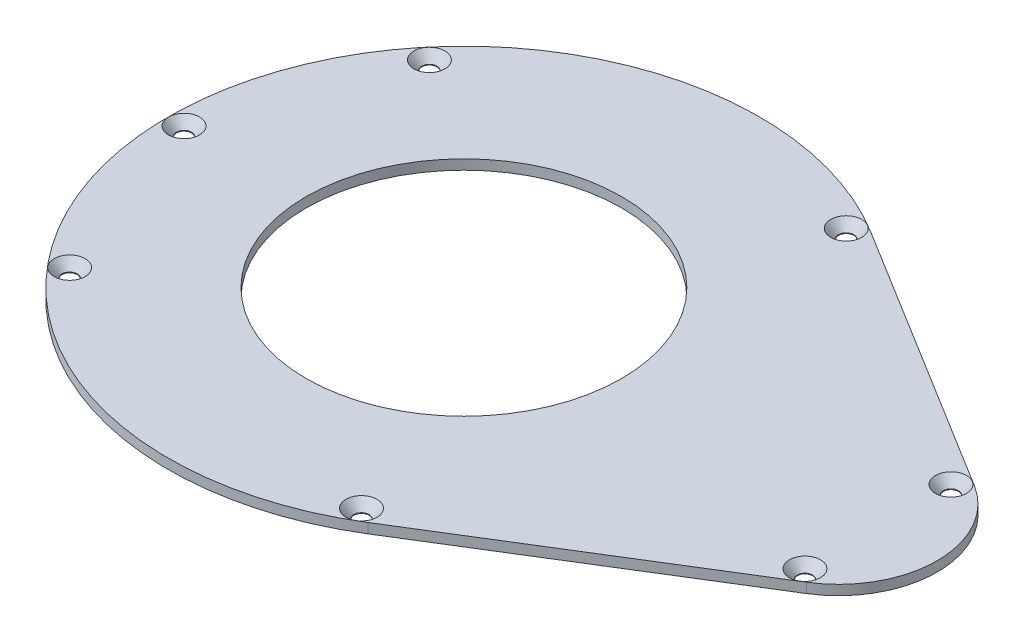
SolidWorks part; units mm, degrees
material "6061-T6 (SS)"
ref_plane "Front Plane" through (0, 0, 0) normal (0, 0, 1) x (1, 0, 0)
ref_plane "Top Plane" through (0, 0, 0) normal (0, 1, 0) x (1, 0, 0)
ref_plane "Right Plane" through (0, 0, 0) normal (1, 0, 0) x (0, 0, -1)
sketch "Sketch1" plane through (0, 0, 0) normal (0, 1, 0) x (1, 0, 0)
  circle A0 centre (0, 0) radius 47.625
  dimension "D1" = 95.25
extrude "Boss-Extrude1" add sketch "Sketch1" along normal blind 24.13
sketch "Sketch2" plane through (0, 0, 0) normal (0, -1, 0) x (1, 0, 0)
  circle A0 centre (0, 0) radius 46.0375
  circle A1 centre (0, 0) radius 47.625 construction
  dimension "D1" = 1.5875
extrude "Cut-Extrude1" cut sketch "Sketch2" against normal offset from surface (20.955 mm away) 3.175 up to face at (0, 24.13, 47.625)
sketch "Sketch3" plane through (0, 20.955, 0) normal (0, -1, 0) x (1, 0, 0)
  circle A0 centre (0, 0) radius 30.48
  dimension "D1" = 60.96
extrude "Cut-Extrude2" cut sketch "Sketch3" against normal through all
sketch "Sketch4" plane through (0, 24.13, 0) normal (0, 1, 0) x (1, 0, 0)
  line L0 (25.0479, 40.5061) -> (68.7175, 13.502)
  line L1 (25.0479, -40.5061) -> (68.7175, -13.502)
  arc A0 (68.7175, -13.502) -> (68.7175, 13.502) centre (60.3682, 0) ccw
  circle A1 centre (0, 0) radius 47.625 construction
  arc A2 (25.0479, -40.5061) -> (25.0479, 40.5061) centre (0, 0) ccw
  dimension "D2" = 31.75
  dimension "D1" = 60.3682
extrude "Boss-Extrude2" add sketch "Sketch4" against normal up to surface (24.13 mm away) up to face at (0, 0, -46.0375)
sketch "Sketch5" plane through (0, 0, 0) normal (0, -1, 0) x (1, 0, 0)
  line L4 (24.2129, -39.1559) -> (67.8825, -12.1518)
  line L5 (67.8825, 12.1518) -> (24.2129, 39.1559)
  line L6 (24.2129, -39.1559) -> (67.8825, -12.1518)
  line L7 (67.8825, 12.1518) -> (24.2129, 39.1559)
  circle A1 centre (0, 0) radius 46.0375 construction
  arc A2 (67.8825, -12.1518) -> (67.8825, 12.1518) centre (60.3682, 0) ccw
  arc A3 (67.8825, -12.1518) -> (67.8825, 12.1518) centre (60.3682, 0) ccw
  arc A4 (24.2129, -39.1559) -> (24.2129, 39.1559) centre (0, 0) ccw
  dimension "D1" = 1.5875
extrude "Cut-Extrude3" cut sketch "Sketch5" against normal up to surface (20.955 mm away) up to face at (0, 20.955, -30.48)
sketch "Sketch6" plane through (0, 20.955, 0) normal (0, -1, 0) x (1, 0, 0)
  line L0 (67.8825, 12.1518) -> (24.2129, 39.1559) construction
  line L1 (24.2129, -39.1559) -> (67.8825, -12.1518) construction
  line L2 (53.1536, 21.2598) -> (46.0477, 25.6539)
  line L3 (46.0477, -25.6539) -> (53.1536, -21.2598)
  line L4 (68.7175, 13.502) -> (25.0479, 40.5061) construction
  line L5 (25.0479, -40.5061) -> (68.7175, -13.502) construction
  line L6 (68.7175, 13.502) -> (46.8827, 27.0041)
  line L7 (46.8827, -27.0041) -> (68.7175, -13.502)
  line L8 (46.0477, 25.6539) -> (46.8827, 27.0041)
  line L9 (46.8827, -27.0041) -> (46.0477, -25.6539)
  arc A0 (53.332, 10.5727) -> (53.332, -10.5727) centre (60.3682, 0) ccw
  arc A2 (68.7175, -13.502) -> (68.7175, 13.502) centre (60.3682, 0) ccw construction
  arc A3 (68.7175, -13.502) -> (68.7175, 13.502) centre (60.3682, 0) ccw
  arc A4 (53.1536, -21.2598) -> (53.332, -10.5727) centre (49.8138, -15.859) ccw
  arc A5 (53.1536, 21.2598) -> (53.332, 10.5727) centre (49.8138, 15.859) cw
  dimension "D1" = 6.35
  dimension "D2" = 12.7
extrude "Boss-Extrude3" add sketch "Sketch6" along normal blind 3.81
sketch "Sketch7" plane through (0, 24.13, 0) normal (0, 1, 0) x (1, 0, 0)
  circle A0 centre (60.3682, 0) radius 11.176
  dimension "D1" = 22.352
extrude "Cut-Extrude4" cut sketch "Sketch7" against normal blind 3.81
chamfer "Chamfer1" distance 0.762 angle 45 1 edges at (60.3682, 24.13, 11.176)
sketch "Sketch8" plane through (0, 20.32, 0) normal (0, 1, 0) x (1, 0, 0)
  circle A0 centre (60.3682, 0) radius 5.08
  dimension "D1" = 10.16
extrude "Cut-Extrude5" cut sketch "Sketch8" against normal through all
hole_wizard "CSK for M2.5 Flat Head Machine Screw1" positions "Sketch10" profile "Sketch9" countersink size "M2.5" standard "Ansi Metric" end condition through all
sketch "Sketch10" plane through (0, 17.145, 0) normal (0, -1, 0) x (1, 0, 0)
  line L0 (60.3682, 0) -> (76.2432, 0) construction
  arc A0 (68.7175, -13.502) -> (68.7175, 13.502) centre (60.3682, 0) ccw construction
  point P0 (67.3682, 0)
  dimension "D1" = 7
sketch "Sketch9" plane through (67.3682, 17.145, 0) normal (1, 0, 0) x (0, 0, -1)
  line L0 (0, 0) -> (0, 6.985)
  line L1 (0, 6.985) -> (1.45, 6.985)
  line L2 (1.45, 6.985) -> (1.45, 1.3)
  line L3 (1.45, 1.3) -> (2.75, 0)
  line L5 (2.75, 0) -> (0, 0)
  line L6 (-1.45, 1.3) -> (-2.75, 0) construction
  line L11 (0, -6.35) -> (0, 107.95) construction
  dimension "Thru Hole Dia." = 2.9
  dimension "Thru Hole Depth" = 6.985
  dimension "Near C'Sink Dia." = 5.5
  dimension "Near C'Sink Angle" = 90
pattern_circular "CirPattern1" count 3 over 360 about axis through (60.3682, 0, 0) along (0, 1, 0) of "CSK for M2.5 Flat Head Machine Screw1"
sketch "Sketch11" plane through (0, 24.13, 0) normal (0, 1, 0) x (1, 0, 0)
  line L0 (68.7175, 13.502) -> (25.0479, 40.5061) construction
  line L1 (-25.4, -31.75) -> (25.4, -31.75) construction
  line L2 (-25.4, -31.75) -> (-25.4, -16.8485) construction
  line L3 (-25.4, 31.75) -> (25.4, 31.75) construction
  line L4 (25.4, -31.75) -> (25.4, 31.75) construction
  line L5 (-25.4, -31.75) -> (25.4, 31.75) construction
  line L6 (-25.4, 31.75) -> (25.4, -31.75) construction
  line L7 (-30.8389, 27.3989) -> (-23.9758, 18.82)
  line L8 (-19.9611, 36.1011) -> (-13.098, 27.5222)
  line L9 (19.7293, 36.2866) -> (12.8217, 27.652)
  line L10 (31.0707, 27.2134) -> (24.1631, 18.5789)
  line L11 (-25.4, 16.8485) -> (-25.4, 31.75) construction
  arc A0 (-19.9611, 36.1011) -> (-30.8389, 27.3989) centre (-25.4, 31.75) ccw
  arc A3 (25.0479, 40.5061) -> (25.0479, -40.5061) centre (0, 0) ccw construction
  arc A4 (31.0707, 27.2134) -> (19.7293, 36.2866) centre (25.4, 31.75) ccw
  circle A6 centre (0, 0) radius 30.48 construction
  arc A7 (-13.098, 27.5222) -> (-23.9758, 18.82) centre (0, 0) ccw
  arc A8 (24.1631, 18.5789) -> (12.8217, 27.652) centre (0, 0) ccw
  point P0 (0, 0)
  dimension "D1" = 50.8
  dimension "D2" = 63.5
extrude "Boss-Extrude4" add sketch "Sketch11" along normal blind 5.588
mirror "Mirror1" about plane through (0, 0, 0) normal (0, 0, 1) of "Boss-Extrude4"
sketch "Sketch12" plane through (0, 24.13, 0) normal (0, 1, 0) x (1, 0, 0)
  circle A1 centre (0, 0) radius 30.48
  arc A2 (12.8217, 27.652) -> (-13.098, 27.5222) centre (0, 0) ccw construction
  circle A3 centre (0, 0) radius 32.0675
  dimension "D1" = 1.5875
extrude "Boss-Extrude5" add sketch "Sketch12" along normal up to surface (5.588 mm away) up to face at (-23.1822, 29.718, -28.9777)
fillet "Fillet2" radius 3.175 8 edges at (-24.993, 26.924, 20.0916) (-14.1153, 26.924, 28.7938) (13.8412, 26.924, 28.9265) (25.1827, 26.924, 19.8534) (25.1827, 26.924, -19.8534) (13.8412, 26.924, -28.9265) (-14.1153, 26.924, -28.7938) (-24.993, 26.924, -20.0916)
hole_wizard "#10-32 Tapped Hole1" positions "Sketch14" profile "Sketch15" tap size "#10-32" standard "Ansi Inch" end condition up to next
sketch "Sketch14" plane through (0, 29.718, 0) normal (0, 1, 0) x (-1, 0, 0)
  point P0 (25.4, -31.75)
  point P1 (-25.4, -31.75)
  point P4 (25.4, 31.75)
  point P7 (-25.4, 31.75)
sketch "Sketch15" plane through (-25.4, 29.718, -31.75) normal (1, 0, 0) x (0, 0, 1)
  line L0 (0, 0) -> (0, 8.763)
  line L1 (0, 8.763) -> (2.0193, 8.763)
  line L2 (2.0193, 8.763) -> (2.0193, 0)
  line L5 (2.0193, 0) -> (0, 0)
  line L11 (0, -6.35) -> (0, 107.95) construction
  dimension "Thru Tap Drill Dia." = 4.0386
  dimension "Thru Tap Drill Depth" = 8.763
cosmetic thread "Hole Thread1" parameters "D2"=4.826
cosmetic thread "Hole Thread2" parameters "D2"=4.826
cosmetic thread "Hole Thread3" parameters "D2"=4.826
cosmetic thread "Hole Thread4" parameters "D2"=4.826
hole_wizard "#4 Clearance Hole1" positions "Sketch18" profile "Sketch17" hole size "#4" standard "Ansi Inch"
sketch "Sketch18" plane through (0, 24.13, 0) normal (0, 1, 0) x (-1, 0, 0)
  point P0 (0, -35.56)
  dimension "D1" = 35.56
sketch "Sketch17" plane through (0, 24.13, -35.56) normal (1, 0, 0) x (0, 0, 1)
  line L0 (0, 0) -> (0, 84.0386)
  line L1 (0, 84.0386) -> (1.6319, 83.058)
  line L2 (1.6319, 83.058) -> (1.6319, 0)
  line L5 (1.6319, 0) -> (0, 0)
  line L10 (0, 84.0386) -> (-1.632, 83.058) construction
  line L11 (0, -6.35) -> (0, 107.95) construction
  dimension "Hole Dia." = 3.2639
  dimension "Hole Depth" = 83.058
  dimension "Drill Angle" = 118
pattern_circular "CirPattern2" count 6 over 360 about axis through (0, 0, 0) along (0, 1, 0) of "#4 Clearance Hole1"
sketch "Sketch19" plane through (0, 0, 0) normal (0, -1, 0) x (1, 0, 0)
  line L0 (68.7175, 13.502) -> (25.0479, 40.5061) construction
  line L1 (-34.5371, 28.9801) -> (0, 0) construction
  line L2 (0, 0) -> (22.5425, 39.0448) construction
  line L3 (0, 0) -> (66.7027, 11.7615) construction
  line L4 (0, 0) -> (76.2432, 0) construction
  circle A0 centre (-45.085, 0) radius 2.54
  arc A1 (25.0479, 40.5061) -> (25.0479, -40.5061) centre (0, 0) ccw construction
  circle A2 centre (-34.5371, 28.9801) radius 2.54
  circle A3 centre (66.7027, 11.7615) radius 2.54
  circle A4 centre (22.5425, 39.0448) radius 2.54
  arc A5 (68.7175, -13.502) -> (68.7175, 13.502) centre (60.3682, 0) ccw construction
  circle A6 centre (66.7027, -11.7615) radius 2.54
  circle A7 centre (22.5425, -39.0448) radius 2.54
  circle A8 centre (-34.5371, -28.9801) radius 2.54
  dimension "D1" = 5.08
  dimension "D2" = 10
  dimension "D3" = 60
  dimension "D4" = 140
extrude "Boss-Extrude6" add sketch "Sketch19" against normal up to surface (20.955 mm away) up to face at (-30.7959, 20.955, -16.1481)
fillet "Fillet3" radius 3.175 14 edges at (20.9281, 10.4775, 41.0057) (25.0498, 10.4775, 38.6384) (65.201, 8.5725, 13.81) (69.1886, 8.5725, 11.2398) (69.1886, 8.5725, -11.2398) (65.201, 8.5725, -13.81) (25.0498, 10.4775, -38.6384) (20.9281, 10.4775, -41.0057) (-33.6907, 10.4775, -31.3749) (-36.7486, 10.4775, -27.7307) (-45.976, 10.4775, -2.3786) (-45.976, 10.4775, 2.3786) (-36.7486, 10.4775, 27.7307) (-33.6907, 10.4775, 31.3749)
hole_wizard "#4-40 Tapped Hole1" positions "Sketch21" profile "Sketch20" tap size "#4-40" standard "Ansi Inch"
sketch "Sketch21" plane through (0, 0, 0) normal (0, -1, 0) x (1, 0, 0)
  point P0 (-34.5371, 28.9801)
  point P1 (22.5425, 39.0448)
  point P4 (66.7027, 11.7615)
  point P7 (66.7027, -11.7615)
  point P10 (22.5425, -39.0448)
  point P13 (-34.5371, -28.9801)
  point P16 (-45.085, 0)
sketch "Sketch20" plane through (-34.5371, 0, 28.9801) normal (1, 0, 0) x (0, 0, -1)
  line L0 (0, 0) -> (0, 8.2992)
  line L1 (0, 8.2992) -> (1.1303, 7.62)
  line L2 (1.1303, 7.62) -> (1.1303, 0)
  line L5 (1.1303, 0) -> (0, 0)
  line L10 (0, 8.2992) -> (-1.1303, 7.62) construction
  line L11 (0, -6.35) -> (0, 107.95) construction
  dimension "Tap Drill Dia." = 2.2606
  dimension "Tap Drill Depth" = 7.62
  dimension "Drill Angle" = 118
cosmetic thread "Hole Thread5" parameters "D1"=5.588, "D2"=2.8448
cosmetic thread "Hole Thread6" parameters "D1"=5.588, "D2"=2.8448
cosmetic thread "Hole Thread7" parameters "D1"=5.588, "D2"=2.8448
cosmetic thread "Hole Thread8" parameters "D1"=5.588, "D2"=2.8448
cosmetic thread "Hole Thread9" parameters "D1"=5.588, "D2"=2.8448
cosmetic thread "Hole Thread10" parameters "D1"=5.588, "D2"=2.8448
cosmetic thread "Hole Thread11" parameters "D1"=5.588, "D2"=2.8448
sketch "Sketch22" plane through (0, 0, 0) normal (0, -1, 0) x (1, 0, 0)
  line L2 (68.7175, 13.502) -> (25.0479, 40.5061)
  line L3 (25.0479, -40.5061) -> (68.7175, -13.502)
  line L4 (68.7175, 13.502) -> (25.0479, 40.5061)
  line L5 (25.0479, -40.5061) -> (68.7175, -13.502)
  arc A2 (25.0479, 40.5061) -> (25.0479, -40.5061) centre (0, 0) ccw
  arc A3 (68.7175, -13.502) -> (68.7175, 13.502) centre (60.3682, 0) ccw
  arc A4 (25.0479, 40.5061) -> (25.0479, -40.5061) centre (0, 0) ccw
  arc A5 (68.7175, -13.502) -> (68.7175, 13.502) centre (60.3682, 0) ccw
  point P2 (-34.5371, 28.9801)
  point P3 (22.5425, 39.0448)
  point P9 (-45.085, 0)
  point P11 (-34.5371, -28.9801)
  point P13 (66.7027, 11.7615)
  point P15 (22.5425, -39.0448)
  point P16 (66.7027, -11.7615)
  dimension "D1" = 0
extrude "Boss-Extrude8" add sketch "Sketch22" along normal blind 1.5875
sketch "Sketch23" plane through (0, 29.718, 0) normal (0, 1, 0) x (1, 0, 0)
  line L1 (29.2194, -37.9265) -> (68.7175, -13.502) construction
  line L2 (68.7175, 13.502) -> (29.2194, 37.9265) construction
  line L5 (29.2194, 37.9265) -> (25.0479, 40.5061) construction
  line L10 (25.0479, -40.5061) -> (29.2194, -37.9265) construction
  line L13 (29.2194, -37.9265) -> (68.7175, -13.502)
  line L14 (68.7175, 13.502) -> (29.2194, 37.9265)
  line L17 (29.2194, 37.9265) -> (25.0479, 40.5061)
  line L22 (25.0479, -40.5061) -> (29.2194, -37.9265)
  arc A3 (68.7175, -13.502) -> (68.7175, 13.502) centre (60.3682, 0) ccw construction
  arc A9 (25.0479, 40.5061) -> (-29.7511, 37.1889) centre (0, 0) ccw construction
  arc A16 (-29.7511, 37.1889) -> (-29.7511, -37.1889) centre (0, 0) ccw construction
  arc A21 (-29.7511, -37.1889) -> (25.0479, -40.5061) centre (0, 0) ccw construction
  arc A27 (68.7175, -13.502) -> (68.7175, 13.502) centre (60.3682, 0) ccw
  arc A33 (25.0479, 40.5061) -> (-29.7511, 37.1889) centre (0, 0) ccw
  arc A40 (-29.7511, 37.1889) -> (-29.7511, -37.1889) centre (0, 0) ccw
  arc A45 (-29.7511, -37.1889) -> (25.0479, -40.5061) centre (0, 0) ccw
extrude "Cut-Extrude6" cut sketch "Sketch23" against normal offset from surface (29.718 mm away) 1.5875 up to face at (30.5959, -1.5875, 0)
hole_wizard "CSK for #2 Flat Head Socket Cap Screw1" positions "Sketch25" profile "Sketch24" countersink size "#2" standard "Ansi Inch" end condition through all
sketch "Sketch25" plane through (0, 0, 0) normal (0, 1, 0) x (-1, 0, 0)
  point P0 (-22.5425, -39.0448)
  point P1 (34.5371, -28.9801)
  point P4 (45.085, 0)
  point P7 (34.5371, 28.9801)
  point P10 (-22.5425, 39.0448)
  point P13 (-66.7027, 11.7615)
  point P16 (-66.7027, -11.7615)
sketch "Sketch24" plane through (22.5425, 0, -39.0448) normal (1, 0, 0) x (0, 0, 1)
  line L0 (0, 0) -> (0, 1.5875)
  line L1 (0, 1.5875) -> (1.2192, 1.5875)
  line L2 (1.2192, 1.5875) -> (1.2192, 1.4756)
  line L3 (1.2192, 1.4756) -> (2.5019, 0)
  line L5 (2.5019, 0) -> (0, 0)
  line L6 (-1.2192, 1.4756) -> (-2.5019, 0) construction
  line L11 (0, -6.35) -> (0, 107.95) construction
  dimension "Thru Hole Dia." = 2.4384
  dimension "Thru Hole Depth" = 1.5875
  dimension "Near C'Sink Dia." = 5.0038
  dimension "Near C'Sink Angle" = 82
sketch "Sketch26" plane through (0, 0, 0) normal (0, 1, 0) x (1, 0, 0)
  circle A0 centre (0, 0) radius 25.4
  dimension "D1" = 50.8
extrude "Cut-Extrude7" cut sketch "Sketch26" against normal blind 1.5875
